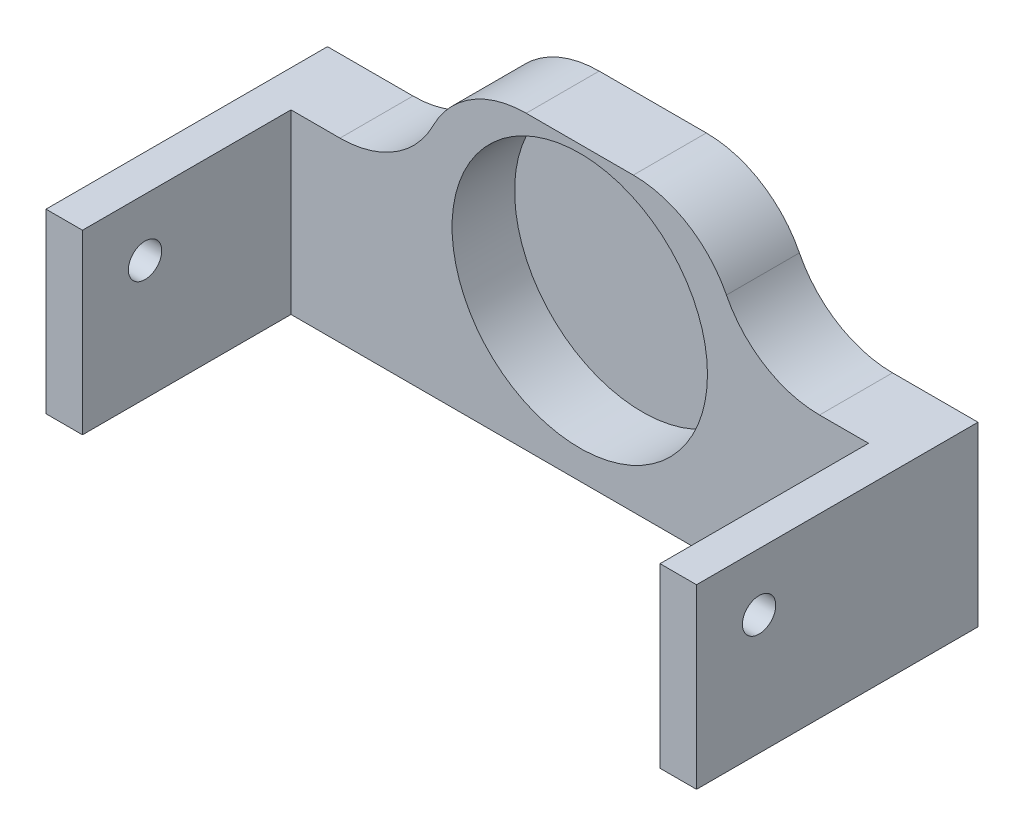
SolidWorks part; units mm, degrees
ref_plane "Front Plane" through (0, 0, 0) normal (0, 0, 1) x (1, 0, 0)
ref_plane "Top Plane" through (0, 0, 0) normal (0, 1, 0) x (1, 0, 0)
ref_plane "Right Plane" through (0, 0, 0) normal (1, 0, 0) x (0, 0, -1)
sketch "Sketch1" plane through (0, 0, 0) normal (0, 0, 1) x (1, 0, 0)
  line L1 (-16.2332, 6.2473) -> (46.1668, 6.2473)
  line L2 (-16.2332, 6.2473) -> (-16.2332, -21.7527)
  line L3 (-16.2332, -21.7527) -> (46.1668, -21.7527)
  line L4 (46.1668, 6.2473) -> (46.1668, -21.7527)
  point P7 (0, 0)
  dimension "D1" = 62.4
  dimension "D2" = 28
extrude "Boss-Extrude2" add sketch "Sketch1" along normal blind 7
sketch "Sketch3" plane through (0, 0, 7) normal (0, 0, 1) x (1, 0, 0)
  line L0 (46.1668, 6.2473) -> (-16.2332, 6.2473) construction
  circle A0 centre (14.9668, -6.7527) radius 12.25
  dimension "D1" = 24.5
  dimension "D2" = 13
extrude "Cut-Extrude2" cut sketch "Sketch3" against normal blind 6
sketch "Sketch4" plane through (0, 0, 7) normal (0, 0, 1) x (1, 0, 0)
  line L0 (-16.2332, -21.7527) -> (46.1668, -21.7527) construction
  line L1 (-16.2332, 6.2473) -> (1.9668, 6.2473)
  line L2 (-16.2332, 6.2473) -> (-16.2332, -4.7527)
  line L3 (-16.2332, -4.7527) -> (1.9668, -4.7527)
  line L4 (1.9668, 6.2473) -> (1.9668, -4.7527)
  line L5 (46.1668, 6.2473) -> (-16.2332, 6.2473) construction
  line L6 (14.9668, 6.2473) -> (14.9668, -27.0994) construction
  line L7 (46.1668, -4.7527) -> (27.9668, -4.7527)
  line L8 (27.9668, 6.2473) -> (27.9668, -4.7527)
  line L9 (46.1668, 6.2473) -> (27.9668, 6.2473)
  line L10 (46.1668, 6.2473) -> (46.1668, -4.7527)
  point P9 (14.9668, 6.2473)
  dimension "D1" = 17
  dimension "D2" = 13
extrude "Cut-Extrude3" cut sketch "Sketch4" against normal up to next
fillet "Fillet1" radius 10 2 edges at (27.9668, -4.7527, 3.5) (1.9668, -4.7527, 3.5)
fillet "Fillet2" radius 10 2 edges at (27.9668, 6.2473, 3.5) (1.9668, 6.2473, 3.5)
sketch "Sketch5" plane through (0, 0, 7) normal (0, 0, 1) x (1, 0, 0)
  line L0 (-16.2332, -21.7527) -> (46.1668, -21.7527) construction
  line L1 (-16.2332, -4.7527) -> (-12.7332, -4.7527)
  line L2 (-16.2332, -4.7527) -> (-16.2332, -21.7527)
  line L3 (-16.2332, -21.7527) -> (-12.7332, -21.7527)
  line L4 (-12.7332, -4.7527) -> (-12.7332, -21.7527)
  line L6 (46.1668, -4.7527) -> (42.6668, -4.7527)
  line L7 (46.1668, -4.7527) -> (46.1668, -21.7527)
  line L8 (46.1668, -21.7527) -> (42.6668, -21.7527)
  line L9 (42.6668, -4.7527) -> (42.6668, -21.7527)
  dimension "D1" = 3.5
  dimension "D2" = 3.5
extrude "Boss-Extrude3" add sketch "Sketch5" along normal blind 20
sketch "Sketch6" plane through (-16.2332, 0, 0) normal (-1, 0, 0) x (0, 0, 1)
  line L0 (27, -21.7527) -> (0, -21.7527) construction
  line L1 (27, -4.7527) -> (27, -21.7527) construction
  circle A0 centre (21, -10.2527) radius 1.6
  dimension "D1" = 11.5
  dimension "D2" = 6
  dimension "D3" = 3.2
extrude "Cut-Extrude4" cut sketch "Sketch6" against normal through all
